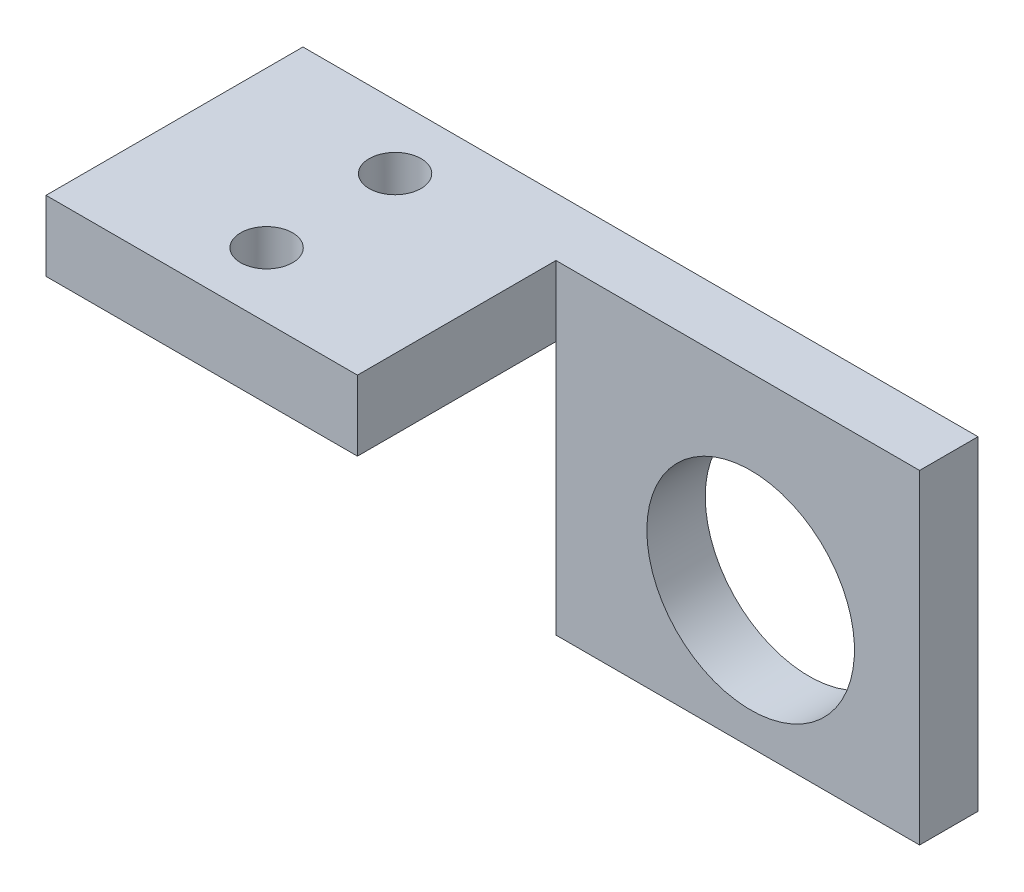
SolidWorks part; units mm, degrees
material "ABS"
ref_plane "Front Plane" through (0, 0, 0) normal (0, 0, 1) x (1, 0, 0)
ref_plane "Top Plane" through (0, 0, 0) normal (0, 1, 0) x (1, 0, 0)
ref_plane "Right Plane" through (0, 0, 0) normal (1, 0, 0) x (0, 0, -1)
sketch "Sketch1" plane through (0, 0, 0) normal (0, 0, 1) x (1, 0, 0)
  line L0 (-24, 15) -> (0, 15)
  line L1 (0, 15) -> (0, 0)
  line L2 (0, 0) -> (93, 0)
  line L3 (93, 0) -> (93, 102.7)
  line L4 (93, 102.7) -> (0, 102.7)
  line L5 (0, 102.7) -> (0, 30)
  line L6 (0, 30) -> (-24, 30)
  line L7 (-24, 30) -> (-24, 15)
  circle A0 centre (15, 10.5) radius 8
  circle A1 centre (70, 72) radius 11
  circle A2 centre (15, 10.5) radius 11
  dimension "D1" = 15
  dimension "D10" = 16
  dimension "D11" = 22
  dimension "D12" = 22
  dimension "D2" = 24
  dimension "D3" = 72.7
  dimension "D4" = 15
  dimension "D5" = 15
  dimension "D6" = 10.5
  dimension "D7" = 82.5061
  dimension "D8" = 72
  dimension "D9" = 93
extrude "Boss-Extrude1" add sketch "Sketch1" along normal blind 4.8 contours A2 L2 L3 L4 L5 L6 L7 L0 L1 A1 | L2 A2 A0
sketch "Sketch2" plane through (0, 0, 4.8) normal (0, 0, 1) x (1, 0, 0)
  line L0 (93, 0) -> (93, 102.7) construction
  line L1 (48.1786, 92.7632) -> (93, 92.7632)
  line L2 (48.1786, 92.7632) -> (48.1786, 52.666)
  line L3 (48.1786, 52.666) -> (93, 52.666)
  line L4 (93, 92.7632) -> (93, 52.666)
  line L5 (48.1786, 92.7632) -> (93, 52.666) construction
  line L6 (48.1786, 52.666) -> (93, 92.7632) construction
  circle A0 centre (70, 72) radius 11
  circle A1 centre (70, 72) radius 4.15
  point P8 (70.5893, 72.7146)
  line M4 (93, 0) -> (93, 102.7)
  circle M10 centre (70, 72) radius 11
  dimension "D1" = 22
  dimension "D2" = 8.3
extrude "Boss-Extrude2" add sketch "Sketch2" along normal blind 8.2 contours L2 L3 L1 M4 M10
sketch "Sketch3" plane through (0, 0, 4.8) normal (0, 0, 1) x (1, 0, 0)
  line L1 (-24, 15) -> (0, 15)
  line L2 (-24, 15) -> (-24, 30)
  line L3 (-24, 30) -> (0, 30)
  line L4 (0, 15) -> (0, 30)
  line L5 (-24, 15) -> (0, 30) construction
  line L6 (-24, 30) -> (0, 15) construction
  line L7 (0, 0) -> (93, 0)
  line L8 (0, 0) -> (0, 52.666)
  line L9 (0, 52.666) -> (93, 52.666)
  line L10 (93, 0) -> (93, 52.666)
  line L11 (0, 0) -> (93, 52.666) construction
  line L12 (0, 52.666) -> (93, 0) construction
  circle A0 centre (15, 10.5) radius 8
  point P4 (-12, 22.5)
  point P11 (46.5, 26.333)
  circle M1 centre (15, 10.5) radius 8
  line M6 (0, 102.7) -> (0, 30)
  line M7 (0, 30) -> (-24, 30)
  line M8 (-24, 30) -> (-24, 15)
  line M9 (-24, 15) -> (0, 15)
  line M10 (0, 15) -> (0, 0)
  line M11 (0, 0) -> (93, 0)
  line M12 (93, 0) -> (93, 52.666)
  line M13 (93, 52.666) -> (48.1786, 52.666)
extrude "Boss-Extrude3" add sketch "Sketch3" along normal blind 5 contours L4 M9 M7 M8 | L9 L4 M6 M10 M11 M12 M13 M1
sketch "Sketch4" plane through (0, 75.2347, 0) normal (0, -1, 0) x (1, 0, 0)
  line L0 (0, 9.8) -> (0, 4.8) construction
  line L1 (0, 4.8) -> (48.1786, 4.8)
  line L2 (0, 4.8) -> (0, 45.3)
  line L3 (0, 45.3) -> (48.1786, 45.3)
  line L4 (48.1786, 4.8) -> (48.1786, 45.3)
  line L5 (0, 4.8) -> (48.1786, 45.3) construction
  line L6 (0, 45.3) -> (48.1786, 4.8) construction
  line L7 (0, 4.8) -> (48.1786, 4.8) construction
  line L8 (48.1786, 13) -> (48.1786, 9.8) construction
  line L9 (0, 0) -> (93, 0) construction
  line L10 (0, 45.3) -> (-5, 45.3)
  line L11 (0, 45.3) -> (0, 0)
  line L12 (0, 0) -> (-5, 0)
  line L13 (-5, 45.3) -> (-5, 0)
  line L14 (0, 45.3) -> (-5, 0) construction
  line L15 (0, 0) -> (-5, 45.3) construction
  circle A0 centre (38.3604, 30.3) radius 6.35
  circle A1 centre (38.3604, 23.3) radius 18.5
  circle A3 centre (53.8604, 23.3) radius 2
  circle A4 centre (46.1104, 9.8766) radius 2
  circle A5 centre (30.6104, 9.8766) radius 2
  point P10 (24.0893, 25.05)
  point P30 (-2.5, 22.65)
  dimension "D1" = 12.7
  dimension "D2" = 15
  dimension "D3" = 4
  dimension "D4" = 4
  dimension "D5" = 4
  dimension "D6" = 5
  dimension "D7" = 0
extrude "Boss-Extrude4" add sketch "Sketch4" along normal blind 5
sketch "Sketch5" plane through (48.1786, 0, 0) normal (1, 0, 0) x (0, 0, -1)
  line L0 (-45.3, 75.2347) -> (-13, 92.7632)
  line L1 (-13, 92.7632) -> (-4.8, 92.7632)
  line L2 (-4.8, 92.7632) -> (-4.8, 70.2347)
  line L3 (-4.8, 70.2347) -> (-45.3, 70.2347)
  line L4 (-45.3, 70.2347) -> (-45.3, 75.2347)
extrude "Boss-Extrude5" add sketch "Sketch5" against normal blind 5
sketch "Sketch6" plane through (0, 0, 4.8) normal (0, 0, 1) x (1, 0, 0)
  line L0 (0, 70.2347) -> (0, 52.666) construction
  line L1 (0, 70.2347) -> (48.1786, 70.2347)
  line L2 (0, 70.2347) -> (0, 52.666)
  line L3 (0, 52.666) -> (48.1786, 52.666)
  line L4 (48.1786, 70.2347) -> (48.1786, 52.666)
  line L5 (0, 70.2347) -> (48.1786, 52.666) construction
  line L6 (0, 52.666) -> (48.1786, 70.2347) construction
  line L7 (0, 70.2347) -> (48.1786, 70.2347) construction
  point P4 (24.0893, 61.4504)
extrude "Boss-Extrude6" add sketch "Sketch6" along normal up to surface (5 mm away)
sketch "Sketch8" plane through (0, 30, 0) normal (0, 1, 0) x (1, 0, 0)
  line L0 (0, 0) -> (-24, -9.8)
  line L1 (-24, -9.8) -> (-24, 0)
  line L2 (-24, 0) -> (0, -9.8)
  circle A0 centre (-12, -4.9) radius 2
  dimension "D1" = 4
extrude "Cut-Extrude1" cut sketch "Sketch8" against normal through all contours A0
sketch "Sketch9" plane through (0, 0, 0) normal (0, 0, -1) x (-1, 0, 0)
  line L0 (0, 0) -> (-93, 0) construction
  line L1 (-93, 102.7) -> (-28.0185, 102.7)
  line L2 (-93, 102.7) -> (-93, 0)
  line L3 (-93, 0) -> (-28.0185, 0)
  line L4 (-28.0185, 102.7) -> (-28.0185, 0)
extrude "Cut-Extrude2" cut sketch "Sketch9" against normal blind 200
sketch "Sketch13" plane through (0, 0, 0) normal (-1, 0, 0) x (0, 0, 1)
  line L0 (9.8, 30) -> (0, 30) construction
  line L1 (0, 102.7) -> (48.03, 102.7)
  line L2 (0, 102.7) -> (0, 30)
  line L3 (0, 30) -> (48.03, 30)
  line L4 (48.03, 102.7) -> (48.03, 30)
  dimension "D1" = 0
extrude "Cut-Extrude5" cut sketch "Sketch13" against normal blind 100
sketch "Sketch14" plane through (0, 0, 9.8) normal (0, 0, 1) x (1, 0, 0)
  line L0 (28.0185, 30) -> (28.0185, 0) construction
  line L1 (-24, 30) -> (28.0185, 30)
  line L2 (-24, 30) -> (-24, 25)
  line L3 (-24, 25) -> (28.0185, 25)
  line L4 (28.0185, 30) -> (28.0185, 25)
  line L6 (-24, 15) -> (0, 15) construction
  dimension "D1" = 10
extrude "Cut-Extrude6" cut sketch "Sketch14" against normal blind 100
sketch "Sketch15" plane through (0, 0, 9.8) normal (0, 0, 1) x (1, 0, 0)
  line L1 (-24, 25) -> (0, 25)
  line L2 (-24, 25) -> (-24, 15)
  line L3 (-24, 15) -> (0, 15)
  line L4 (0, 25) -> (0, 15)
extrude "Boss-Extrude7" add sketch "Sketch15" along normal blind 10
sketch "Sketch16" plane through (0, 25, 0) normal (0, 1, 0) x (1, 0, 0)
  line L0 (0, -19.8) -> (-24, -19.8) construction
  circle A0 centre (-12, -14.8) radius 2
  circle A1 centre (-12, -4.9) radius 2 construction
  dimension "D1" = 4
  dimension "D2" = 5
  dimension "D3" = 0
extrude "Cut-Extrude7" cut sketch "Sketch16" against normal blind 10
sketch "Sketch17" plane through (0, 25, 0) normal (0, 1, 0) x (1, 0, 0)
  line L0 (28.0185, 0) -> (28.0185, -9.8) construction
  line L1 (0, -9.8) -> (28.0185, -9.8)
  line L2 (0, -9.8) -> (0, -4.5)
  line L3 (0, -4.5) -> (28.0185, -4.5)
  line L4 (28.0185, -9.8) -> (28.0185, -4.5)
  line L5 (-24, 0) -> (28.0185, 0) construction
  dimension "D1" = 4.5
extrude "Cut-Extrude11" cut sketch "Sketch17" against normal blind 100
sketch "Sketch18" plane through (0, 0, 0) normal (0, 0, -1) x (-1, 0, 0)
  line L0 (0, 15) -> (0, 0) construction
  line L1 (24, 15) -> (0, 15)
  line L2 (24, 15) -> (24, 19.59)
  line L3 (24, 19.59) -> (0, 19.59)
  line L4 (0, 15) -> (0, 19.59)
  line L5 (24, 15) -> (0, 19.59) construction
  line L6 (24, 19.59) -> (0, 15) construction
  point P4 (12, 17.295)
  dimension "D1" = 4.59
extrude "Cut-Extrude12" cut sketch "Sketch18" against normal through all
